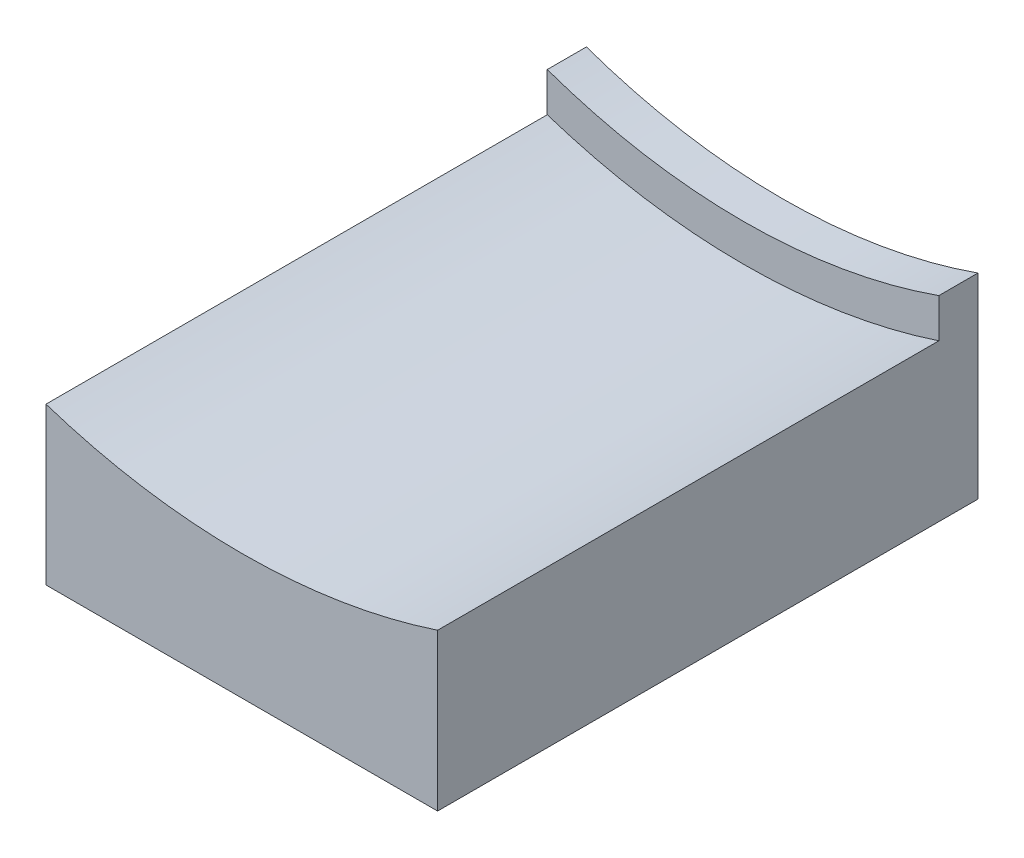
SolidWorks part; units mm, degrees
ref_plane "Front Plane" through (0, 0, 0) normal (0, 0, 1) x (1, 0, 0)
ref_plane "Top Plane" through (0, 0, 0) normal (0, 1, 0) x (1, 0, 0)
ref_plane "Right Plane" through (0, 0, 0) normal (1, 0, 0) x (0, 0, -1)
sketch "Sketch3" plane through (0, 0, 0) normal (0, 0, 1) x (1, 0, 0)
  line L0 (0, 0) -> (50, 0)
  line L1 (0, 0) -> (0, 20)
  line L2 (50, 0) -> (50, 20)
  arc A0 (0, 20) -> (50, 20) centre (25, 95.9934) ccw
  point P7 (-0.552, 13.2247)
  point P8 (0, 0)
  point P9 (25, 0)
  point P10 (25, 89.5766)
  point P11 (0, 0)
  point P12 (0, 0)
  point P13 (50.5492, 13.0586)
  dimension "D2" = 80
  dimension "D1" = 50
  dimension "D3" = 20
extrude "Boss-Extrude1" add sketch "Sketch3" along normal blind 64
sketch "Sketch4" plane through (0, 0, 0) normal (0, 0, -1) x (-1, 0, 0)
  line L0 (-50, 0) -> (0, 0)
  line L1 (0, 0) -> (0, 25)
  line L3 (-50, 0) -> (-50, 25)
  arc A0 (-50, 25) -> (0, 25) centre (-25, 95.9934) ccw
  point P6 (-50, 25)
  point P7 (-50, 25)
  point P9 (-50, 0)
  point P10 (0, 0)
  dimension "D1" = 25
extrude "Boss-Extrude2" add sketch "Sketch4" along normal blind 5
